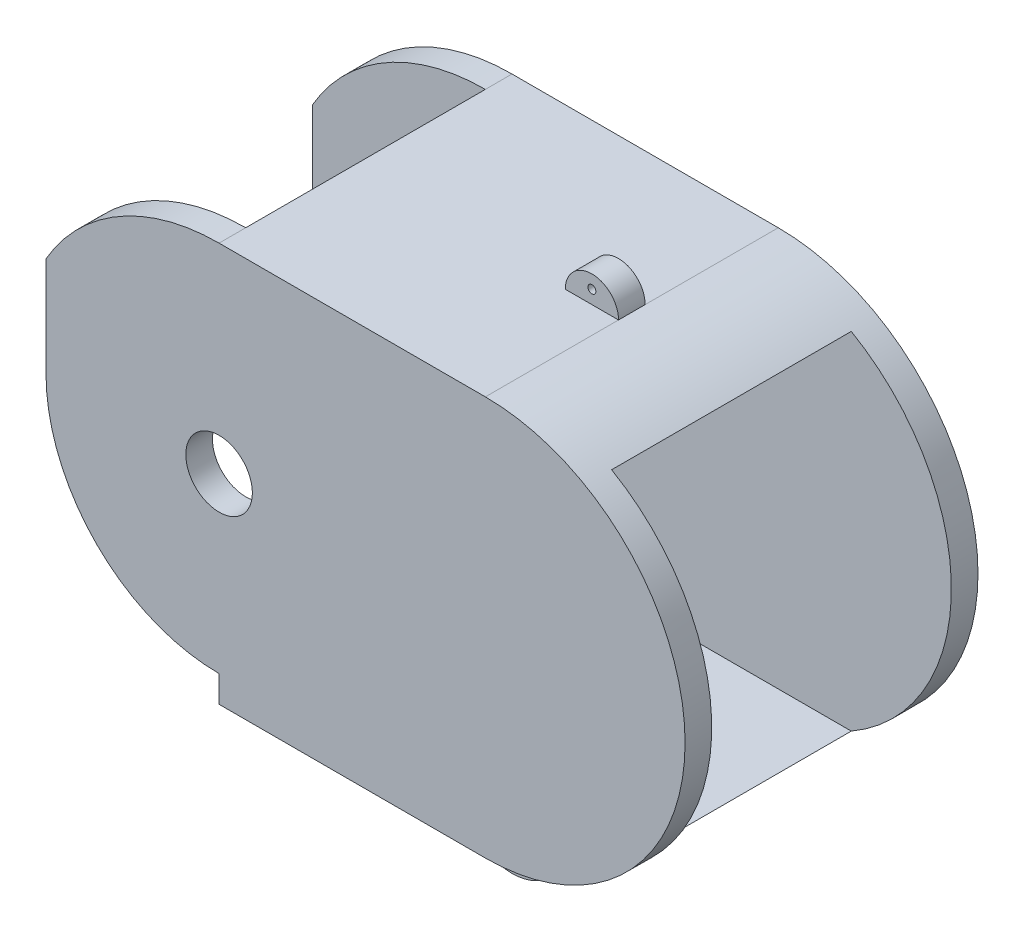
SolidWorks part; units mm, degrees
ref_plane "Front Plane" through (0, 0, 0) normal (0, 0, 1) x (1, 0, 0)
ref_plane "Top Plane" through (0, 0, 0) normal (0, 1, 0) x (1, 0, 0)
ref_plane "Right Plane" through (0, 0, 0) normal (1, 0, 0) x (0, 0, -1)
ref_plane "Right Side Plane" through (0, 0, 9.525) normal (0, 0, 1) x (1, 0, 0)
ref_plane "Inside Plane" through (0, 19.05, 0) normal (0, 1, 0) x (1, 0, 0)
ref_plane "Joint Plane" through (-15.875, 0, 0) normal (1, 0, 0) x (0, 0, -1)
sketch "Sketch1" plane through (0, 0, 0) normal (0, 1, 0) x (1, 0, 0)
  line L1 (-15.875, 9.525) -> (15.875, 9.525)
  line L2 (-15.875, 9.525) -> (-15.875, -9.525)
  line L3 (-15.875, -9.525) -> (15.875, -9.525)
  line L4 (15.875, 9.525) -> (15.875, -9.525)
  dimension "D1" = 31.75
  dimension "D2" = 19.05
  dimension "D3" = 9.525
  dimension "D4" = 15.875
extrude "Boss-Extrude1" add sketch "Sketch1" along normal blind 19.05
sketch "Sketch2" plane through (0, 0, 9.525) normal (0, 0, 1) x (1, 0, 0)
  line L0 (-15.875, 19.05) -> (15.875, 19.05) construction
  line L1 (-15.875, 19.05) -> (-15.875, 0) construction
  line L2 (-15.875, 0) -> (15.875, 0) construction
  line L3 (15.875, 19.05) -> (15.875, 0) construction
  circle A0 centre (-6.35, 9.525) radius 1.5875
  arc A1 (-6.35, 19.05) -> (-6.35, 0) centre (-6.35, 9.525) ccw
  arc A2 (-6.35, 19.05) -> (-6.35, 0) centre (-14.6688, 9.525) ccw
  arc A3 (6.35, 0) -> (6.35, 19.05) centre (6.35, 9.525) ccw
  arc A4 (6.35, 19.05) -> (6.35, 0) centre (13.21, 9.525) cw
extrude "Cut-Extrude2" cut sketch "Sketch2" against normal blind 19.05
sketch "Sketch3" plane through (0, 19.05, 0) normal (0, 1, 0) x (1, 0, 0)
  line L0 (15.875, -9.525) -> (15.875, 9.525) construction
  line L1 (-15.875, 9.525) -> (15.875, 9.525)
  line L2 (-15.875, 9.525) -> (-15.875, 6.985)
  line L3 (-15.875, 6.985) -> (15.875, 6.985)
  line L4 (15.875, 9.525) -> (15.875, 6.985)
  line L5 (-10.4775, -9.525) -> (10.4775, -9.525) construction
  line L6 (-15.875, -9.525) -> (15.875, -9.525)
  line L7 (-15.875, -9.525) -> (-15.875, -6.985)
  line L8 (-15.875, -6.985) -> (15.875, -6.985)
  line L9 (15.875, -9.525) -> (15.875, -6.985)
  line L10 (-6.35, 9.525) -> (-6.35, -9.525) construction
  line L11 (-15.875, 5.715) -> (-6.35, 5.715)
  line L12 (-15.875, 5.715) -> (-15.875, -5.715)
  line L13 (-15.875, -5.715) -> (-6.35, -5.715)
  line L14 (-6.35, 5.715) -> (-6.35, -5.715)
  dimension "D1" = 2.54
  dimension "D2" = 2.54
  dimension "D3" = 1.27
  dimension "D4" = 1.27
extrude "Cut-Extrude3" cut sketch "Sketch3" against normal blind 19.05
sketch "Sketch4" plane through (-15.875, 0, 0) normal (1, 0, 0) x (0, 0, -1)
  line L0 (5.715, 11.1125) -> (5.715, 19.05) construction
  line L1 (5.715, 17.78) -> (-5.715, 17.78)
  line L2 (5.715, 17.78) -> (5.715, 1.27)
  line L3 (5.715, 1.27) -> (-5.715, 1.27)
  line L4 (-5.715, 17.78) -> (-5.715, 1.27)
  line L5 (-5.715, 0) -> (-5.715, 19.05) construction
  line L6 (7.6835, 19.05) -> (-7.6835, 19.05) construction
  line L7 (-5.715, 0) -> (5.715, 0) construction
  dimension "D1" = 1.27
  dimension "D2" = 1.27
extrude "Cut-Extrude4" cut sketch "Sketch4" along normal blind 50.8
sketch "Sketch5" plane through (0, 0, 9.525) normal (0, 0, 1) x (1, 0, 0)
  line L0 (-14.605, 17.4864) -> (-18.3107, 1.27)
  line L2 (-18.3107, 1.27) -> (-18.3107, 0)
  line L3 (-18.3107, 0) -> (-6.35, 0)
  line L4 (-6.35, 1.27) -> (-6.35, 0)
  line L5 (-14.605, 9.525) -> (-14.605, 17.4864)
  arc A1 (-14.605, 9.525) -> (-6.35, 1.27) centre (-6.35, 9.525) ccw
  dimension "D1" = 1.27
extrude "Cut-Extrude5" cut sketch "Sketch5" against normal blind 19.05
sketch "Sketch6" plane through (0, 0, 0) normal (0, 1, 0) x (1, 0, 0)
  line L0 (-6.35, 6.985) -> (-6.35, -6.985) construction
  line L1 (0, -1.905) -> (5.08, -1.905)
  line L2 (0, -1.905) -> (0, 1.905)
  line L3 (0, 1.905) -> (5.08, 1.905)
  line L4 (5.08, -1.905) -> (5.08, 1.905)
  line L5 (6.35, -6.985) -> (-6.35, -6.985) construction
  dimension "D1" = 3.81
  dimension "D2" = 5.08
  dimension "D3" = 6.35
  dimension "D4" = 5.08
extrude "Boss-Extrude2" add sketch "Sketch6" against normal blind 7.62
sketch "Sketch7" plane through (0, 0, 9.525) normal (0, 0, 1) x (1, 0, 0)
  line L4 (0, -2.54) -> (0, 0)
  line L5 (2.9402, 0) -> (5.08, 0)
  arc A0 (5.08, -2.54) -> (2.54, -5.08) centre (2.54, -2.54) cw
  arc A1 (2.54, -5.08) -> (0, -2.54) centre (2.54, -2.54) cw
  arc A2 (5.08, -2.54) -> (3.8035, -1.3339) centre (3.8387, -2.5752) ccw
  arc A3 (3.8035, -1.3339) -> (3.8233, -2.0347) centre (3.8134, -1.6843) ccw
  arc A4 (3.8233, -2.0347) -> (4.455, -2.5752) centre (3.8172, -2.6811) cw
  arc A5 (4.455, -2.5752) -> (2.54, -4.4612) centre (2.3289, -2.3316) cw
  arc A6 (2.54, -4.4612) -> (0.6762, -2.54) centre (2.8343, -2.311) cw
  arc A7 (0.6762, -2.54) -> (2.9402, 0) centre (4.7921, -3.9296) cw
  arc A8 (5.08, 0) -> (0, 0) centre (2.54, -4.4339) cw
extrude "Cut-Extrude6" cut sketch "Sketch7" against normal blind 19.05
sketch "Sketch8" plane through (0, 19.05, 0) normal (0, 1, 0) x (1, 0, 0)
  line L1 (3.81, 0.635) -> (6.35, 0.635)
  line L2 (3.81, 0.635) -> (3.81, -0.635)
  line L3 (3.81, -0.635) -> (6.35, -0.635)
  line L4 (6.35, 0.635) -> (6.35, -0.635)
  dimension "D1" = 1.27
  dimension "D2" = 2.54
  dimension "D3" = 6.35
  dimension "D4" = 0.635
extrude "Boss-Extrude3" add sketch "Sketch8" along normal blind 1.27
sketch "Sketch9" plane through (0, 0, 9.525) normal (0, 0, 1) x (1, 0, 0)
  line L0 (3.81, 19.05) -> (6.35, 19.05) construction
  line L1 (6.35, 20.32) -> (6.35, 19.05) construction
  arc A0 (3.81, 19.05) -> (6.35, 19.05) centre (5.08, 19.05) cw
  circle A1 centre (5.08, 19.685) radius 0.1905
  arc A2 (3.81, 19.05) -> (6.35, 19.05) centre (5.08, 19.7941) cw
  dimension "D1" = 0.635
  dimension "D2" = 1.27
extrude "Cut-Extrude7" cut sketch "Sketch9" against normal blind 19.05
